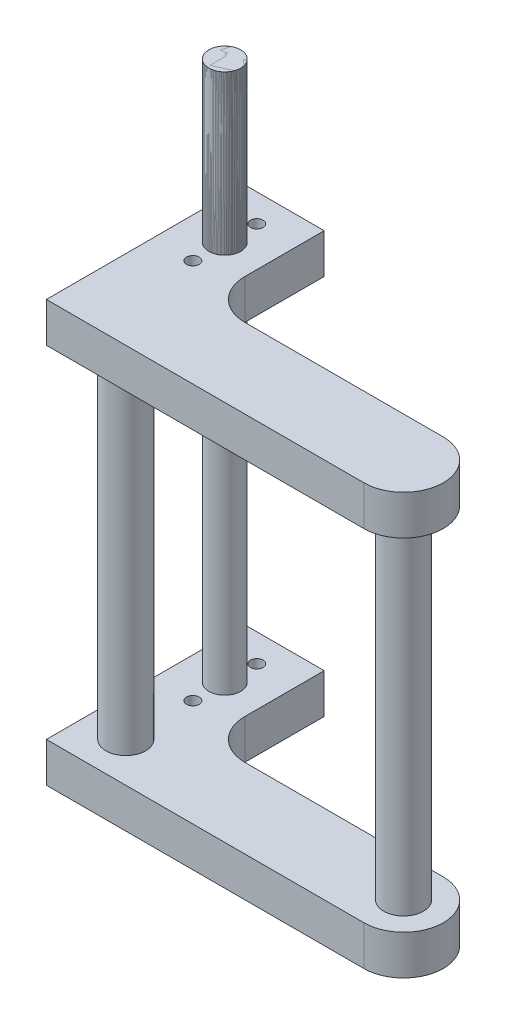
SolidWorks part; units mm, degrees
ref_plane "前视基准面" through (0, 0, 0) normal (0, 0, 1) x (1, 0, 0)
ref_plane "上视基准面" through (0, 0, 0) normal (0, 1, 0) x (1, 0, 0)
ref_plane "右视基准面" through (0, 0, 0) normal (1, 0, 0) x (0, 0, -1)
other "Configuration Table"
sketch "草图1" plane through (0, 0, 0) normal (0, 1, 0) x (1, 0, 0)
  line L0 (0, 0) -> (0, 30)
  line L1 (0, 30) -> (-20, 30)
  line L2 (-20, 30) -> (-20, -20)
  line L3 (-20, -20) -> (60, -20)
  line L4 (0, 0) -> (60, 0)
  line L5 (-10, 23) -> (-10, 6.9) construction
  line L6 (-20, 23) -> (0, 23) construction
  arc A0 (60, 0) -> (60, -20) centre (60, -10) cw
  circle A1 centre (-10, 23) radius 1.6
  circle A2 centre (-10, 6.9) radius 1.6
  circle A3 centre (-10, 14.95) radius 3.75
  circle A4 centre (60, -10) radius 3.75
  point P16 (-10, 23)
  dimension "D5" = 3.2
  dimension "D6" = 3.2
  dimension "D9" = 7.5
  dimension "D10" = 7.5
  dimension "D1" = 60
  dimension "D2" = 30
  dimension "D3" = 20
  dimension "D4" = 20
  dimension "D7" = 7
  dimension "D8" = 16.1
extrude "凸台-拉伸1" add sketch "草图1" along normal blind 10
sketch "草图2" plane through (0, 0, 0) normal (0, -1, 0) x (1, 0, 0)
  line L0 (-10, -14.95) -> (-10, 10) construction
  line L1 (-10, 10) -> (60, 10) construction
  circle A0 centre (-10, 10) radius 5
  circle A1 centre (-10, -14.95) radius 4
  circle A2 centre (60, 10) radius 5
  dimension "D1" = 8
  dimension "D2" = 10
  dimension "D3" = 10
extrude "凸台-拉伸2" add sketch "草图2" against normal blind 106
ref_plane "基准面1" through (0, 53, 0) normal (0, -1, 0) x (-1, 0, 0)
mirror "镜向4" about plane through (0, 53, 0) normal (0, -1, 0) of bodies 107
sketch "草图4" plane through (0, 106, 0) normal (0, 1, 0) x (1, 0, 0)
  circle A0 centre (-10, -10) radius 5 construction
  circle A1 centre (-10, -10) radius 5
  circle A2 centre (-10, 14.95) radius 4 construction
  circle A3 centre (-10, 14.95) radius 4
extrude "凸台-拉伸5" add sketch "草图4" along normal blind 40 separate body contours A3
mirror "镜向1" about plane through (0, 53, 0) normal (0, -1, 0) of "凸台-拉伸1"
sketch "草图3" plane through (0, 106, 0) normal (0, 1, 0) x (1, 0, 0)
  circle A0 centre (-10, 14.95) radius 4 construction
  circle A1 centre (-10, 14.95) radius 4 construction
  circle A2 centre (-10, 14.95) radius 4
extrude "凸台-拉伸3" add sketch "草图3" along normal blind 40
fillet "圆角1" radius 10 2 edges at (0, 5, 0) (0, 101, 0)
